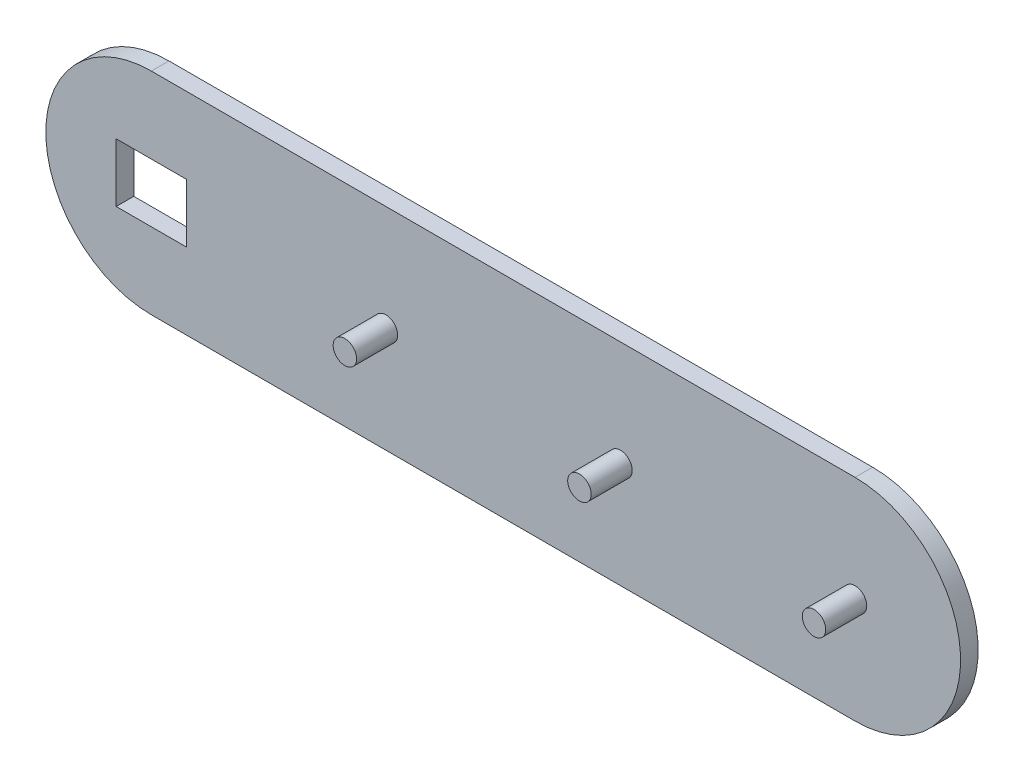
SolidWorks part; units mm, degrees
ref_plane "Front Plane" through (0, 0, 0) normal (0, 0, 1) x (1, 0, 0)
ref_plane "Top Plane" through (0, 0, 0) normal (0, 1, 0) x (1, 0, 0)
ref_plane "Right Plane" through (0, 0, 0) normal (1, 0, 0) x (0, 0, -1)
sketch "Sketch2" plane through (0, 0, 0) normal (0, 0, 1) x (1, 0, 0)
  line L0 (0, 0) -> (120, 0) construction
  line L1 (0, 18) -> (120, 18)
  line L2 (0, -18) -> (120, -18)
  arc A0 (0, 18) -> (0, -18) centre (0, 0) ccw
  arc A1 (120, -18) -> (120, 18) centre (120, 0) ccw
  point P3 (60, 0)
  dimension "D1" = 18
  dimension "D2" = 120
extrude "Boss-Extrude1" add sketch "Sketch2" along normal blind 3
sketch "Sketch3" plane through (0, 0, 3) normal (0, 0, 1) x (1, 0, 0)
  line L1 (-6, 5) -> (6, 5)
  line L2 (-6, 5) -> (-6, -5)
  line L3 (-6, -5) -> (6, -5)
  line L4 (6, 5) -> (6, -5)
  line L5 (-6, 5) -> (6, -5) construction
  line L6 (-6, -5) -> (6, 5) construction
  point P0 (0, 0)
  dimension "D1" = 12
  dimension "D2" = 10
extrude "Cut-Extrude1" cut sketch "Sketch3" against normal blind 3 contours L2 L1 L4 L3
sketch "Sketch5" plane through (0, 0, 3) normal (0, 0, 1) x (1, 0, 0)
  circle A0 centre (0, 0) radius 20
  circle A1 centre (120, 0) radius 2
  dimension "D1" = 40
  dimension "D2" = 4
extrude "Boss-Extrude2" add sketch "Sketch5" along normal blind 7 contours A1
pattern_linear "LPattern1" count 4 spacing 40 along (-1, 0, 0) skipping (3, 0) of "Boss-Extrude2"
